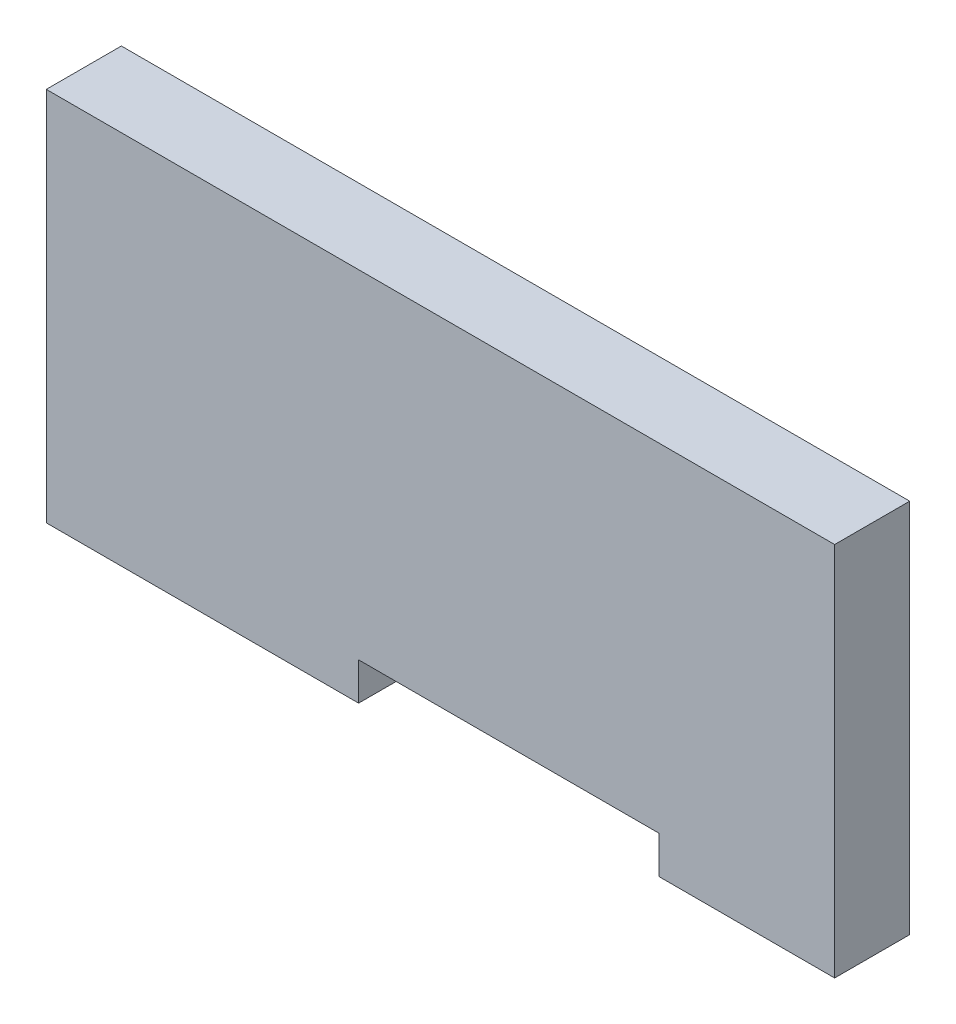
SolidWorks part; units mm, degrees
ref_plane "Front Plane" through (0, 0, 0) normal (0, 0, 1) x (1, 0, 0)
ref_plane "Top Plane" through (0, 0, 0) normal (0, 1, 0) x (1, 0, 0)
ref_plane "Right Plane" through (0, 0, 0) normal (1, 0, 0) x (0, 0, -1)
sketch "Sketch1" plane through (0, 0, 0) normal (0, 0, 1) x (1, 0, 0)
  line L0 (-21.8, -50) -> (-105, -50)
  line L1 (105, -50) -> (58.2, -50)
  line L2 (105, -50) -> (105, 50)
  line L3 (105, 50) -> (-105, 50)
  line L4 (-105, -50) -> (-105, 50)
  line L5 (105, -50) -> (-105, 50) construction
  line L6 (105, 50) -> (-105, -50) construction
  line L8 (58.2, -50) -> (58.2, -40)
  line L9 (58.2, -40) -> (-21.8, -40)
  line L10 (-21.8, -50) -> (-21.8, -40)
  point P0 (0, 0)
  point P5 (0, -50)
  dimension "D1" = 100
  dimension "D2" = 210
extrude "Boss-Extrude1" add sketch "Sketch1" along normal blind 20
